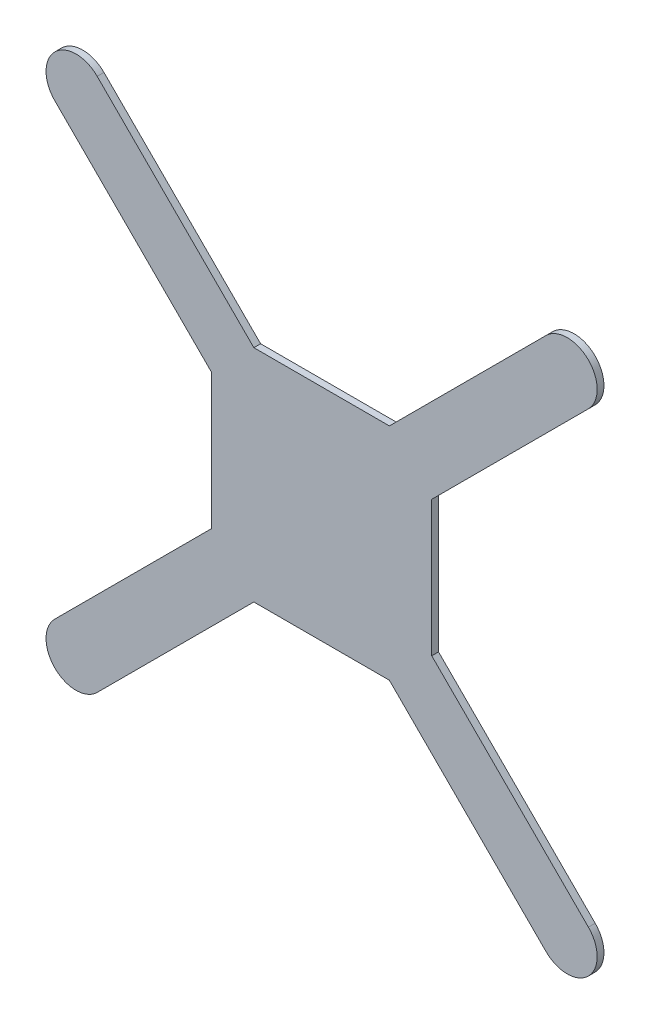
SolidWorks part; units mm, degrees
ref_plane "前视基准面" through (0, 0, 0) normal (0, 0, 1) x (1, 0, 0)
ref_plane "上视基准面" through (0, 0, 0) normal (0, 1, 0) x (1, 0, 0)
ref_plane "右视基准面" through (0, 0, 0) normal (1, 0, 0) x (0, 0, -1)
other "Configuration Table"
sketch "草图1" plane through (0, 0, 0) normal (0, 0, 1) x (1, 0, 0)
  line L0 (0, 0) -> (0, -16.3537) construction
  line L1 (-65, 65) -> (-159.099, 159.099) construction
  line L2 (-40, 65) -> (40, 65)
  line L3 (-65, 40) -> (-65, -40)
  line L4 (-40, -65) -> (40, -65)
  line L5 (65, 40) -> (65, -40)
  line L6 (0, 0) -> (32.5134, 0) construction
  line L7 (40, -65) -> (65, -40)
  line L8 (65, 65) -> (159.099, 159.099) construction
  line L9 (40, 65) -> (65, 40)
  line L10 (-65, 40) -> (-40, 65)
  line L11 (-65, -40) -> (-40, -65)
  line L12 (40, 65) -> (132.4569, 157.4569)
  line L13 (65, 40) -> (157.4569, 132.4569)
  line L14 (65, -40) -> (157.4569, -132.4569)
  line L15 (40, -65) -> (132.4569, -157.4569)
  line L16 (-40, -65) -> (-132.4569, -157.4569)
  line L17 (-65, -40) -> (-157.4569, -132.4569)
  line L18 (-65, 40) -> (-157.4569, 132.4569)
  line L19 (-40, 65) -> (-132.4569, 157.4569)
  arc A0 (132.4569, 157.4569) -> (157.4569, 132.4569) centre (144.9569, 144.9569) cw
  arc A1 (132.4569, -157.4569) -> (157.4569, -132.4569) centre (144.9569, -144.9569) ccw
  arc A2 (-132.4569, -157.4569) -> (-157.4569, -132.4569) centre (-144.9569, -144.9569) cw
  arc A3 (-132.4569, 157.4569) -> (-157.4569, 132.4569) centre (-144.9569, 144.9569) ccw
  point P0 (-65, 65)
  point P1 (65, -65)
  point P3 (-65, -65)
  point P4 (65, 65)
  point P9 (65, 65)
  point P15 (-65, 65)
  point P26 (217.8747, 192.8747)
  point P27 (203.6019, 203.6019)
  point P38 (0, 0)
  dimension "D3" = 45
  dimension "D2" = 45
  dimension "D8" = 130
  dimension "D9" = 410
  dimension "D1" = 45
  dimension "D4" = 45
  dimension "D5" = 45
  dimension "D6" = 25
  dimension "D7" = 25
extrude "凸台-拉伸1" add sketch "草图1" along normal blind 4 contours A2 L16 L11 L17 | L19 A3 L18 L10 | L3 L11 L4 L7 L5 L9 L2 L10 | L15 A1 L14 L7 | A0 L12 L9 L13
